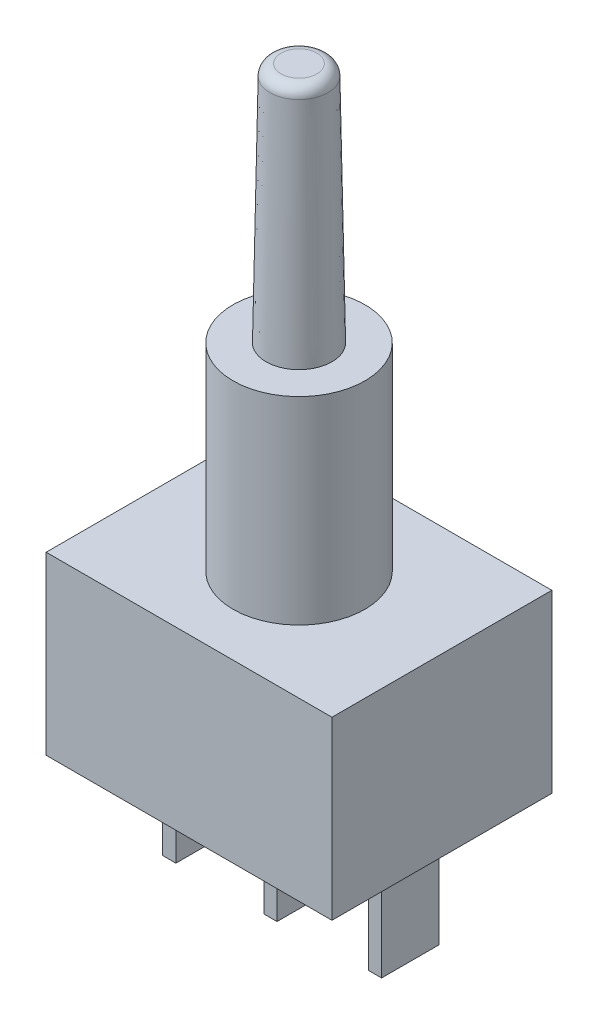
SolidWorks part; units mm, degrees
ref_plane "前视基准面" through (0, 0, 0) normal (0, 0, 1) x (1, 0, 0)
ref_plane "上视基准面" through (0, 0, 0) normal (0, 1, 0) x (1, 0, 0)
ref_plane "右视基准面" through (0, 0, 0) normal (1, 0, 0) x (0, 0, -1)
sketch "草图1" plane through (0, 0, 0) normal (0, 1, 0) x (1, 0, 0)
  line L1 (-6.5, 5) -> (6.5, 5)
  line L2 (-6.5, 5) -> (-6.5, -5)
  line L3 (-6.5, -5) -> (6.5, -5)
  line L4 (6.5, 5) -> (6.5, -5)
  line L5 (-6.5, 5) -> (6.5, -5) construction
  line L6 (-6.5, -5) -> (6.5, 5) construction
  point P0 (0, 0)
  dimension "D1" = 13
  dimension "D2" = 10
extrude "凸台-拉伸1" add sketch "草图1" along normal blind 8
sketch "草图2" plane through (0, 8, 0) normal (0, 1, 0) x (1, 0, 0)
  circle A0 centre (0, 0) radius 3
  dimension "D1" = 6
extrude "凸台-拉伸2" add sketch "草图2" along normal blind 9
cosmetic thread "装饰螺纹线1" parameters "D2"=4.917
sketch "草图6" plane through (0, 17, 0) normal (0, 1, 0) x (1, 0, 0)
  circle A0 centre (0, 0) radius 1.5
  dimension "D1" = 3
extrude "凸台-拉伸3" add sketch "草图6" along normal blind 11 draft 1
fillet "圆角1" radius 0.5 1 edges at (0, 28, 1.308)
sketch "草图7" plane through (0, 0, 0) normal (0, -1, 0) x (1, 0, 0)
  line L1 (-4.9, 1.3) -> (-4.3, 1.3)
  line L2 (-4.9, 1.3) -> (-4.9, -1.3)
  line L3 (-4.9, -1.3) -> (-4.3, -1.3)
  line L4 (-4.3, 1.3) -> (-4.3, -1.3)
  line L5 (-4.9, 1.3) -> (-4.3, -1.3) construction
  line L6 (-4.9, -1.3) -> (-4.3, 1.3) construction
  line L7 (-0.3, 1.3) -> (0.3, 1.3)
  line L8 (-0.3, 1.3) -> (-0.3, -1.3)
  line L9 (-0.3, -1.3) -> (0.3, -1.3)
  line L10 (0.3, 1.3) -> (0.3, -1.3)
  line L11 (-0.3, 1.3) -> (0.3, -1.3) construction
  line L12 (-0.3, -1.3) -> (0.3, 1.3) construction
  line L13 (4.3, 1.1435) -> (4.9, 1.1435)
  line L14 (4.3, 1.1435) -> (4.3, -1.4565)
  line L15 (4.3, -1.4565) -> (4.9, -1.4565)
  line L16 (4.9, 1.1435) -> (4.9, -1.4565)
  line L17 (4.3, 1.1435) -> (4.9, -1.4565) construction
  line L18 (4.3, -1.4565) -> (4.9, 1.1435) construction
  point P0 (-4.6, 0)
  point P5 (4.6, -0.1565)
  point P7 (0, 0)
  dimension "D1" = 0.6
  dimension "D2" = 2.6
  dimension "D3" = 0.6
  dimension "D4" = 2.6
  dimension "D5" = 0.6
  dimension "D6" = 2.6
  dimension "D7" = 4
  dimension "D8" = 4
extrude "凸台-拉伸4" add sketch "草图7" along normal blind 5
